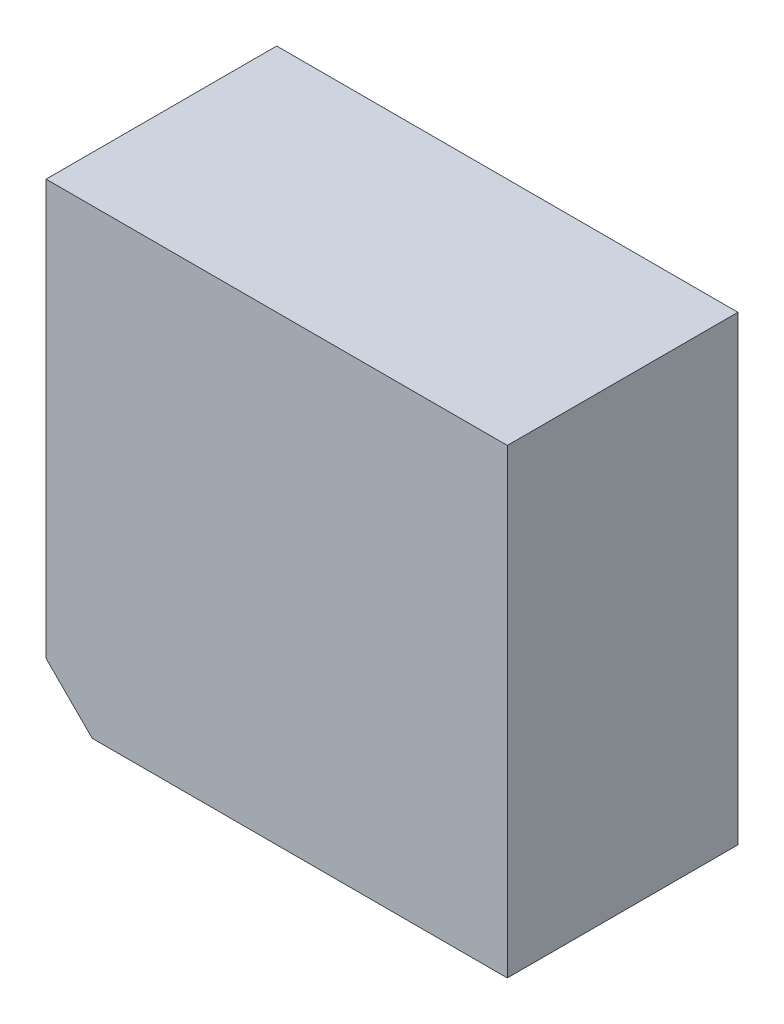
SolidWorks part; units mm, degrees
ref_plane "前视基准面" through (0, 0, 0) normal (0, 0, 1) x (1, 0, 0)
ref_plane "上视基准面" through (0, 0, 0) normal (0, 1, 0) x (1, 0, 0)
ref_plane "右视基准面" through (0, 0, 0) normal (1, 0, 0) x (0, 0, -1)
other "Configuration Table"
sketch "草图1" plane through (0, 0, 0) normal (0, 0, 1) x (1, 0, 0)
  line L1 (0, 0) -> (20, 0)
  line L2 (0, 0) -> (0, 20)
  line L3 (0, 20) -> (20, 20)
  line L4 (20, 0) -> (20, 20)
extrude "BaseBox" add sketch "草图1" along normal blind 10
chamfer "ChamferAngleDistance" distance 2 angle 45 1 edges at (0, 0, 5)
